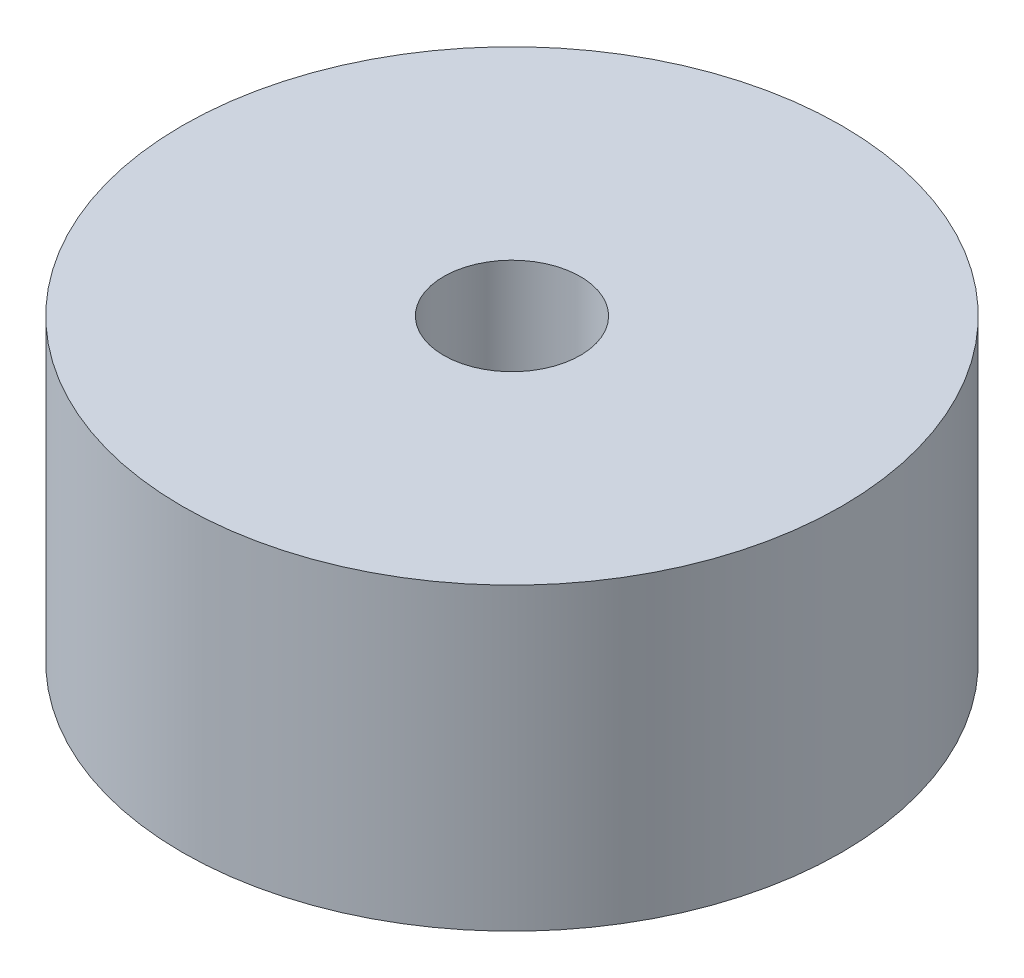
SolidWorks part; units mm, degrees
ref_plane "Front Plane" through (0, 0, 0) normal (0, 0, 1) x (1, 0, 0)
ref_plane "Top Plane" through (0, 0, 0) normal (0, 1, 0) x (1, 0, 0)
ref_plane "Right Plane" through (0, 0, 0) normal (1, 0, 0) x (0, 0, -1)
sketch "Sketch1" plane through (0, 0, 0) normal (0, 1, 0) x (1, 0, 0)
  line L0 (0, 0) -> (99.948, 0) construction
  circle A1 centre (0, 0) radius 1.14
  circle A2 centre (0, 0) radius 5.5
  dimension "D1" = 2.28
  dimension "D2" = 11
extrude "Boss-Extrude1" add sketch "Sketch1" along normal blind 5
